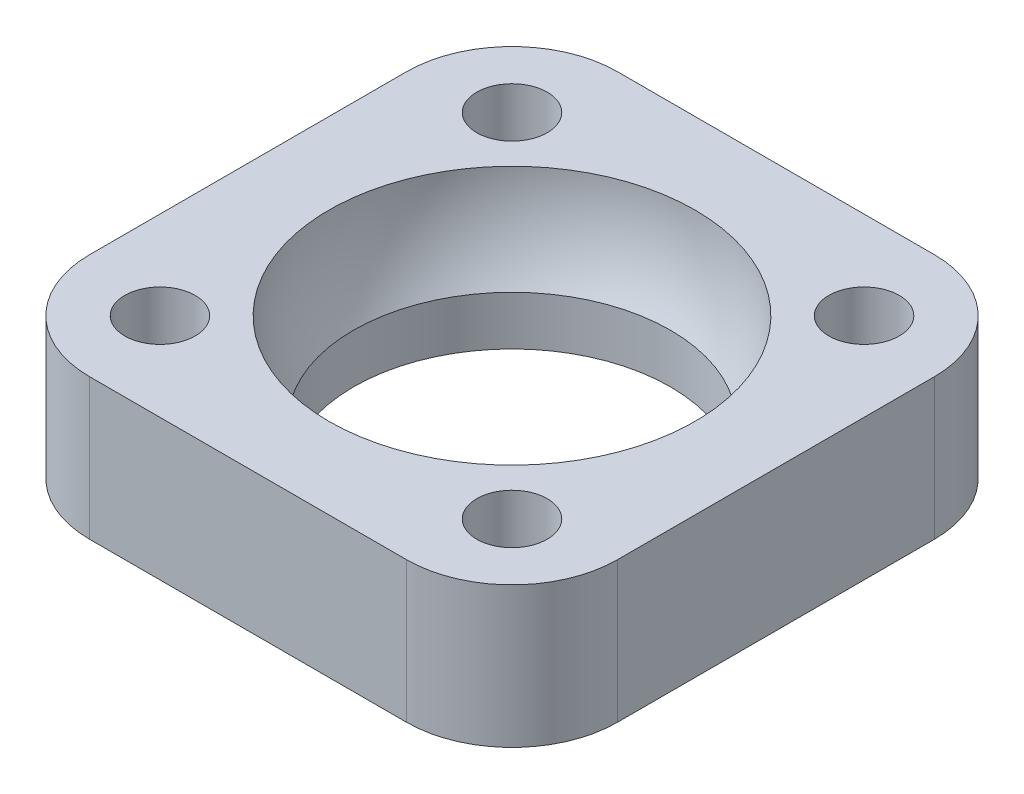
SolidWorks part; units mm, degrees
ref_plane "Front" through (0, 0, 0) normal (0, 0, 1) x (1, 0, 0)
ref_plane "Top" through (0, 0, 0) normal (0, 1, 0) x (1, 0, 0)
ref_plane "Right" through (0, 0, 0) normal (1, 0, 0) x (0, 0, -1)
sketch "Sketch1" plane through (0, 0, 0) normal (0, 1, 0) x (1, 0, 0)
  line L1 (0, 0) -> (15, 0)
  line L2 (0, 0) -> (0, -15)
  line L3 (0, -15) -> (15, -15)
  line L4 (15, 0) -> (15, -15)
  dimension "D1" = 15
  dimension "D2" = 15
extrude "Boss-Extrude1" add sketch "Sketch1" along normal blind 4
sketch "Sketch2" plane through (0, 4, 0) normal (0, 1, 0) x (1, 0, 0)
  line L0 (0, -15) -> (15, -15) construction
  line L1 (15, -15) -> (15, 0) construction
  line L2 (12.7, -7.5) -> (2.3, -7.5)
  arc A0 (2.3, -7.5) -> (12.7, -7.5) centre (7.5, -7.5) ccw
  dimension "D1" = 10.4
  dimension "D2" = 7.5
  dimension "D3" = 7.5
revolve "Cut-Revolve1" cut sketch "Sketch2" angle 360 about L2
sketch "Sketch3" plane through (0, 4, 0) normal (0, 1, 0) x (1, 0, 0)
  line L0 (0, -15) -> (15, -15) construction
  line L1 (0, 0) -> (0, -15) construction
  circle A0 centre (2.5, -12.5) radius 1
  circle A1 centre (12.5, -12.5) radius 1
  circle A2 centre (12.5, -2.5) radius 1
  circle A3 centre (2.5, -2.5) radius 1
  dimension "D1" = 2
  dimension "D2" = 2.5
  dimension "D3" = 2.5
  dimension "D4" = 2
  dimension "D5" = 2
extrude "Cut-Extrude1" cut sketch "Sketch3" against normal through all
sketch "Sketch4" plane through (0, 0, 0) normal (0, -1, 0) x (-1, 0, 0)
  circle A0 centre (-7.5, -7.5) radius 4.5
  dimension "D1" = 9
extrude "Cut-Extrude2" cut sketch "Sketch4" against normal through all
fillet "Fillet1" radius 3 4 edges at (15, 2, 15) (0, 2, 15) (15, 2, 0) (0, 2, 0)
